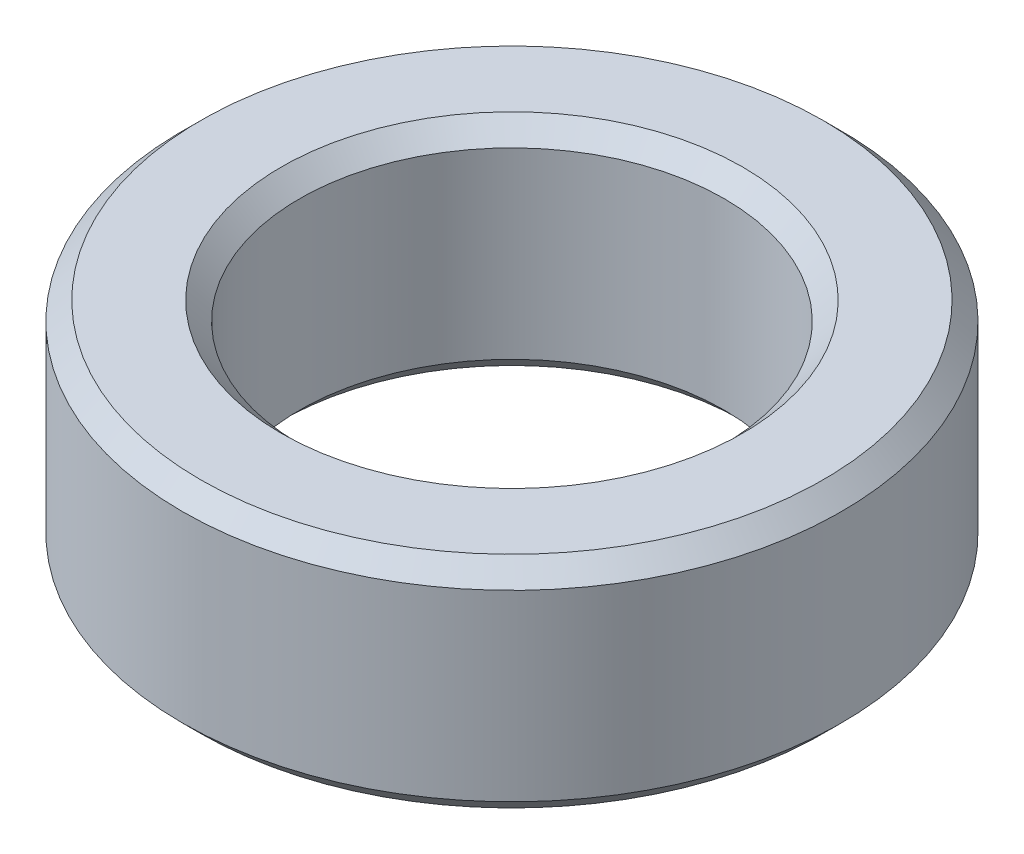
SolidWorks part; units mm, degrees
ref_plane "Front Plane" through (0, 0, 0) normal (0, 0, 1) x (1, 0, 0)
ref_plane "Top Plane" through (0, 0, 0) normal (0, 1, 0) x (1, 0, 0)
ref_plane "Right Plane" through (0, 0, 0) normal (1, 0, 0) x (0, 0, -1)
sketch "Sketch1" plane through (0, 0, 0) normal (0, 1, 0) x (1, 0, 0)
  circle A0 centre (0, 0) radius 2.9
  circle A1 centre (0, 0) radius 4.5
  dimension "D1" = 5.8
  dimension "D2" = 9
extrude "Boss-Extrude1" add sketch "Sketch1" along normal blind 3
chamfer "Chamfer1" distance 0.25 angle 45 4 edges at (0, 3, 4.5) (0, 0, 4.5) (0, 0, 2.9) (0, 3, 2.9)
